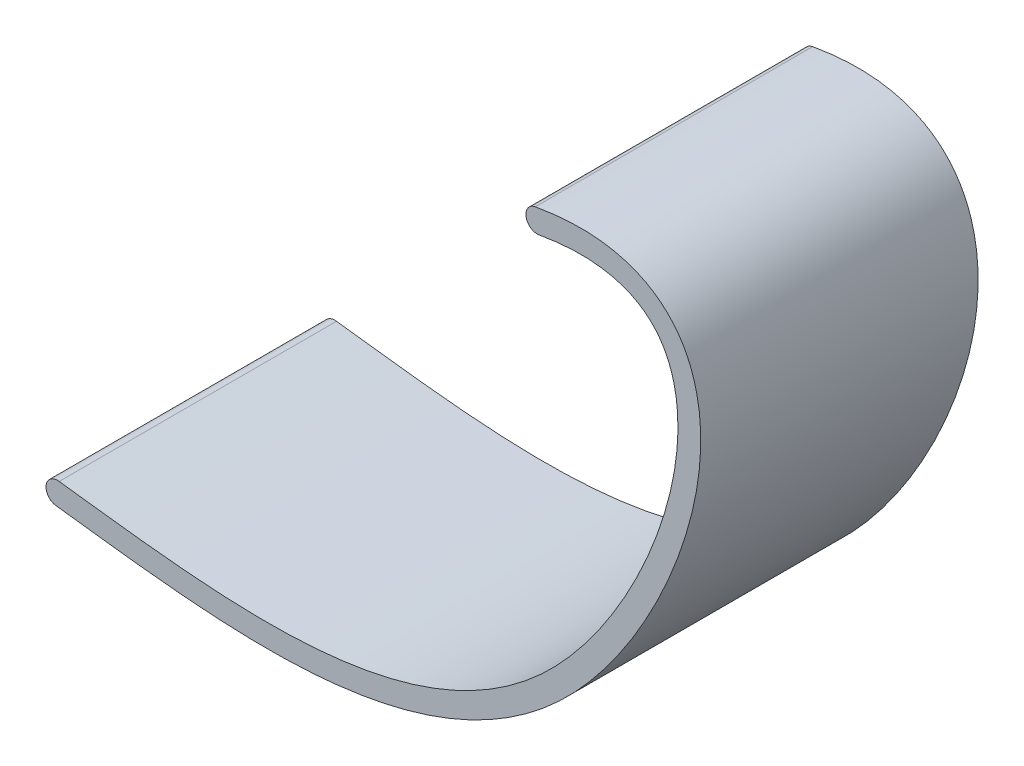
SolidWorks part; units mm, degrees
ref_plane "Front Plane" through (0, 0, 0) normal (0, 0, 1) x (1, 0, 0)
ref_plane "Top Plane" through (0, 0, 0) normal (0, 1, 0) x (1, 0, 0)
ref_plane "Right Plane" through (0, 0, 0) normal (1, 0, 0) x (0, 0, -1)
sketch "Sketch1" plane through (0, 0, 0) normal (0, 0, 1) x (1, 0, 0)
  arc A0 (10.0064, -8.7237) -> (9.3918, -8.976) centre (10.2858, -10.2789) ccw
  arc A1 (-56.3736, -75.0714) -> (-56.756, -78.2216) centre (-56.6161, -76.6403) ccw
  circle A2 centre (10.287, -10.287) radius 1.5875 construction
  arc A3 (9.3918, -8.976) -> (10.5675, -11.8503) centre (10.2906, -10.286) ccw
  spline S2 degree 3 poles (10.5675, -11.8503) (11.0643, -11.7611) (12.0805, -11.5977) (13.9682, -11.3709) (16.1669, -11.2497) (18.5189, -11.351) (21.2955, -11.7854) (24.1117, -12.8347) (26.6017, -14.7551) (28.38, -17.3068) (29.8881, -21.5631) (30.1363, -28.3287) (27.9997, -37.7909) (23.8494, -47.6113) (18.1417, -56.8869) (11.394, -64.665) (4.0362, -70.2613) (-6.5194, -75.3788) (-17.9888, -77.4951) (-29.8767, -77.6816) (-38.8563, -77.1259) (-46.2666, -76.3162) (-52.0993, -75.5992) (-54.9424, -75.2451) (-56.3736, -75.0714) knots 0 0 0 0 0.007812 0.015625 0.03125 0.046875 0.0625 0.09375 0.125 0.15625 0.1875 0.25 0.3125 0.375 0.4375 0.5 0.5625 0.625 0.75 0.8125 0.875 0.9375 0.96875 1 1 1 1
  spline S4 degree 3 poles (10.0064, -8.7237) (10.5424, -8.6274) (11.6354, -8.4516) (13.6947, -8.2039) (16.1318, -8.0682) (18.816, -8.1816) (22.0936, -8.6906) (25.6323, -9.9872) (28.9457, -12.532) (31.262, -15.8806) (32.6334, -19.807) (33.1771, -24.1612) (32.935, -30.4027) (31.0255, -38.8001) (26.6782, -49.0757) (20.7293, -58.7487) (13.602, -66.9757) (5.7101, -72.9846) (-2.7645, -77.0885) (-11.6404, -79.5614) (-20.7557, -80.715) (-29.9668, -80.8566) (-39.1423, -80.2874) (-46.6366, -79.4679) (-52.4948, -78.7478) (-55.3272, -78.395) (-56.756, -78.2216) knots 0 0 0 0 0.007812 0.015625 0.03125 0.046875 0.0625 0.09375 0.125 0.15625 0.1875 0.21875 0.25 0.3125 0.375 0.4375 0.5 0.5625 0.625 0.6875 0.75 0.8125 0.875 0.9375 0.96875 1 1 1 1
  dimension "D2" = 66.38
  dimension "D3" = 66.3477
extrude "Boss-Extrude1" add sketch "Sketch1" along normal blind 38.6715 contours S4 A1 S2 A3 A0
